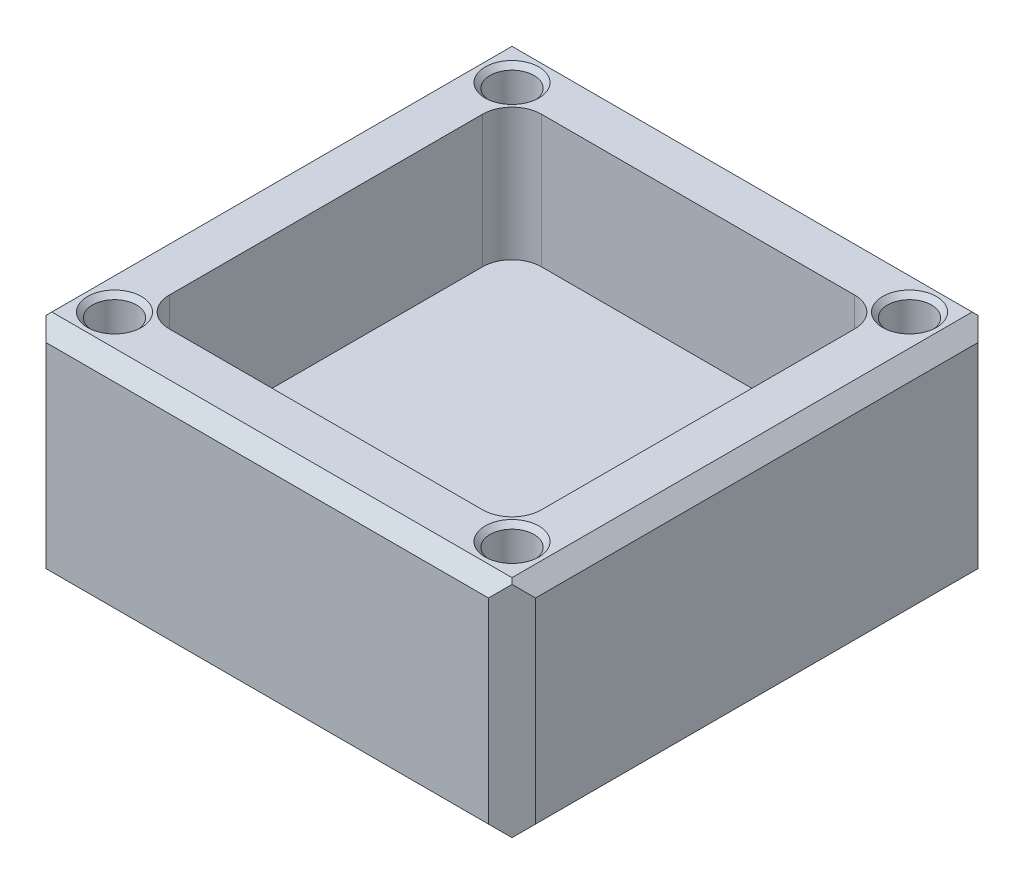
SolidWorks part; units mm, degrees
ref_plane "Front Plane" through (0, 0, 0) normal (0, 0, 1) x (1, 0, 0)
ref_plane "Top Plane" through (0, 0, 0) normal (0, 1, 0) x (1, 0, 0)
ref_plane "Right Plane" through (0, 0, 0) normal (1, 0, 0) x (0, 0, -1)
sketch "Sketch1" plane through (0, 0, 0) normal (0, 0, 1) x (1, 0, 0)
  line L0 (0, -21.5) -> (3.5, -25)
  line L1 (1.5, 0) -> (48.5, 0)
  line L2 (0, -1.5) -> (0, -21.5)
  line L3 (3.5, -25) -> (46.5, -25)
  line L4 (50, -1.5) -> (50, -21.5)
  line L5 (1.5, 0) -> (0, -1.5)
  line L6 (25, -25) -> (25, -15.9605) construction
  line L7 (50, -21.5) -> (46.5, -25)
  line L8 (48.5, 0) -> (50, -1.5)
  dimension "D1" = 47
  dimension "D2" = 20
  dimension "D3" = 2.1213
  dimension "D4" = 4.9497
  dimension "D5" = 43
  dimension "D6" = 50
  dimension "D7" = 0
  dimension "D8" = 50
extrude "Boss-Extrude1" add sketch "Sketch1" along normal blind 50
sketch "Sketch2" plane through (0, 0, 0) normal (-1, 0, 0) x (0, 0, 1)
  line L0 (48.5, 0) -> (50, -1.5)
  line L1 (50, 0) -> (0, 0) construction
  line L2 (50, -1.5) -> (50, -21.5) construction
  line L3 (48.5, 0) -> (50, 0)
  line L4 (50, 0) -> (50, -1.5)
  line L5 (25, -1.5) -> (25, -9.5541) construction
  line L6 (50, -1.5) -> (0, -1.5) construction
  line L7 (50, -21.5) -> (46.5, -25)
  line L8 (50, -25) -> (0, -25) construction
  line L9 (46.5, -25) -> (50, -25)
  line L10 (50, -25) -> (50, -21.5)
  line L11 (1.5, 0) -> (0, 0)
  line L12 (1.5, 0) -> (0, -1.5)
  line L13 (0, 0) -> (0, -1.5)
  line L14 (3.5, -25) -> (0, -25)
  line L15 (0, -21.5) -> (3.5, -25)
  line L16 (0, -25) -> (0, -21.5)
  dimension "D1" = 1.5
  dimension "D2" = 1.5
  dimension "D3" = 3.5
extrude "Cut-Extrude1" cut sketch "Sketch2" against normal blind 50
sketch "Sketch3" plane through (0, 0, 0) normal (0, 1, 0) x (1, 0, 0)
  line L0 (1.5, -48.5) -> (1.5, -1.5) construction
  line L1 (9, -6) -> (41, -6)
  line L2 (6, -9) -> (6, -41)
  line L3 (9, -44) -> (41, -44)
  line L4 (44, -9) -> (44, -41)
  line L5 (6.8787, -6.8787) -> (43.1213, -43.1213) construction
  line L6 (6.8787, -43.1213) -> (43.1213, -6.8787) construction
  line L7 (41, -6) -> (41, -10.4053) construction
  line L9 (48.5, -1.5) -> (1.5, -1.5) construction
  arc A0 (44, -9) -> (41, -6) centre (41, -9) ccw
  arc A1 (41, -44) -> (44, -41) centre (41, -41) ccw
  arc A2 (6, -41) -> (9, -44) centre (9, -41) ccw
  arc A3 (9, -6) -> (6, -9) centre (9, -9) ccw
  point P0 (25, -25)
  point P13 (41, -9)
  point P26 (25, -25)
  dimension "D5" = 3
  dimension "D1" = 4
  dimension "D3" = 4.5
  dimension "D4" = 4.5
  dimension "D6" = 3
extrude "Cut-Extrude2" cut sketch "Sketch3" against normal blind 13.5
sketch "Sketch4" plane through (0, 0, 0) normal (0, 1, 0) x (1, 0, 0)
  line L0 (1.5, -1.5) -> (7.5242, -7.5242) construction
  line L1 (48.5, -1.5) -> (1.5, -1.5) construction
  line L2 (1.5, -48.5) -> (1.5, -1.5) construction
  line L3 (25, -1.5) -> (25, -38.5821) construction
  line L4 (1.5, -25) -> (39.9662, -25) construction
  circle A0 centre (4.7, -4.7) radius 2.25
  circle A1 centre (45.3, -4.7) radius 2.25
  circle A2 centre (45.3, -45.3) radius 2.25
  circle A3 centre (4.7, -45.3) radius 2.25
  point P22 (25, -25)
  dimension "D3" = 4.5
  dimension "D1" = 3.2
  dimension "D2" = 3.2
  dimension "D4" = 4
extrude "Cut-Extrude3" cut sketch "Sketch4" against normal blind 18
hole_wizard "CSK for M2.5 Countersunk Flat Head Screw1" positions "3DSketch2" profile "Sketch6" countersink size "M2.5" standard "ISO"
sketch3d "3DSketch2"
  line L0 (4.7, -18, 4.7) -> (4.7, 0, 4.7) construction
  line L1 (45.3, -18, 4.7) -> (45.3, 0, 4.7) construction
  line L2 (45.3, -18, 45.3) -> (45.3, 0, 45.3) construction
  line L3 (4.7, -18, 45.3) -> (4.7, 0, 45.3) construction
  point P0 (4.7, 0, 4.7)
  point P4 (45.3, 0, 4.7)
  point P8 (45.3, 0, 45.3)
  point P12 (4.7, 0, 45.3)
sketch "Sketch6" plane through (4.7, 0, 4.7) normal (1, 0, 0) x (0, 0, 1)
  line L0 (0, 0) -> (0, 1.72)
  line L1 (0, 1.72) -> (1.45, 0.8488)
  line L2 (1.45, 0.8488) -> (1.45, 1.3)
  line L3 (1.45, 1.3) -> (2.75, 0)
  line L5 (2.75, 0) -> (0, 0)
  line L6 (-1.45, 1.3) -> (-2.75, 0) construction
  line L10 (0, 1.72) -> (-1.45, 0.8488) construction
  line L11 (0, -6.35) -> (0, 107.95) construction
  dimension "Hole Dia." = 2.9
  dimension "Hole Depth" = 1.72
  dimension "Near C'Sink Dia." = 5.5
  dimension "Near C'Sink Angle" = 90
  dimension "Drill Angle" = 118
sketch "Sketch7" plane through (0, 0, 0) normal (0, 1, 0) x (1, 0, 0)
  line L0 (0, -2.4042) -> (2.4042, 0)
  line L1 (0, -50) -> (0, 0) construction
  line L2 (50, 0) -> (0, 0) construction
  line L3 (25, -6) -> (25, -30.3143) construction
  line L4 (41, -6) -> (9, -6) construction
  line L5 (6, -25) -> (36.2639, -25) construction
  line L6 (6, -9) -> (6, -41) construction
  line L7 (2.4042, 0) -> (0, 0)
  line L8 (0, 0) -> (0, -2.4042)
  line L9 (50, 0) -> (47.5958, 0)
  line L10 (47.5958, 0) -> (50, -2.4042)
  line L11 (50, -2.4042) -> (50, 0)
  line L12 (50, -50) -> (50, -47.5958)
  line L13 (50, -47.5958) -> (47.5958, -50)
  line L14 (47.5958, -50) -> (50, -50)
  line L15 (0, -50) -> (2.4042, -50)
  line L16 (2.4042, -50) -> (0, -47.5958)
  line L17 (0, -47.5958) -> (0, -50)
  point P15 (25, -25)
  point P17 (2.4042, 0)
  point P30 (25, -25)
  dimension "D1" = 1.7
  dimension "D2" = 4
extrude "Cut-Extrude4" cut sketch "Sketch7" against normal through all
sketch "Sketch8" plane through (0, 0, 0) normal (-1, 0, 0) x (0, 0, 1)
  line L0 (8.9042, -14) -> (41.0958, -14) construction
  line L1 (47.5958, -21.5) -> (2.4042, -21.5) construction
  line L2 (47.5958, -21.5) -> (47.5958, -1.5) construction
  line L3 (2.4042, -21.5) -> (2.4042, -1.5) construction
  text T0 "Napolitaantje\r\n"
  dimension "D1" = 7.5
  dimension "D2" = 6.5
  dimension "D3" = 6.5
extrude "Cut-Extrude5" cut sketch "Sketch8" against normal blind 1
